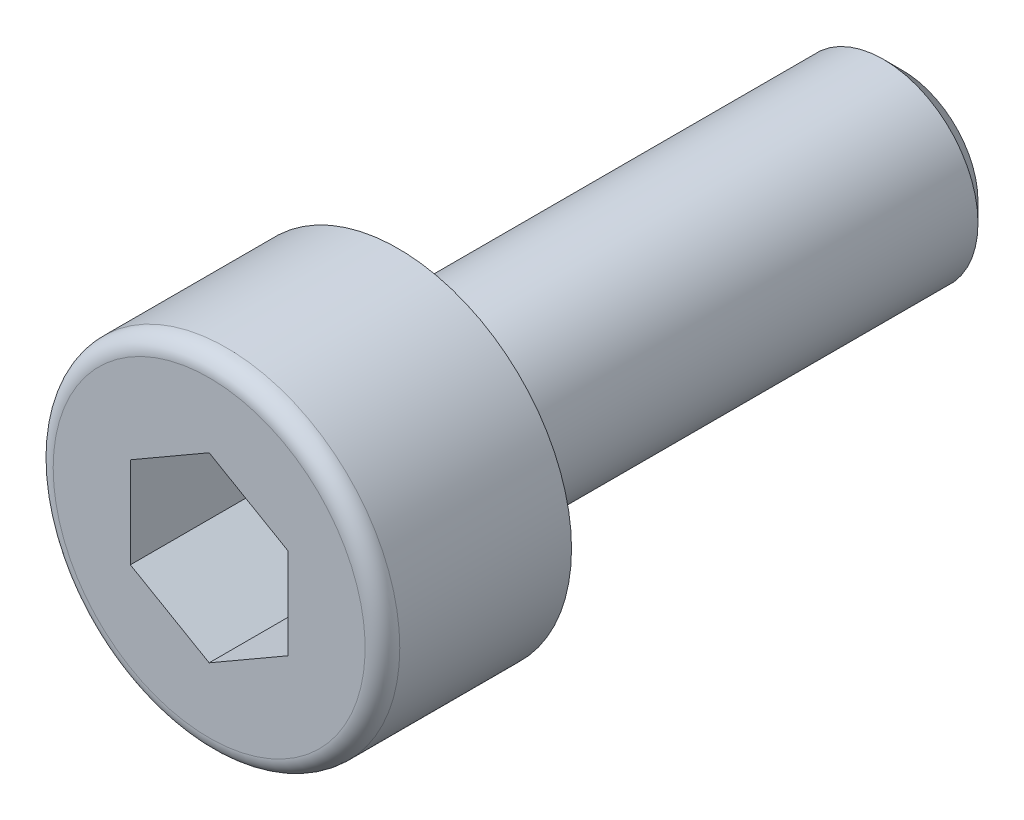
SolidWorks part; units mm, degrees
material "普通碳钢"
ref_plane "前视基准面" through (0, 0, 0) normal (0, 0, 1) x (1, 0, 0)
ref_plane "上视基准面" through (0, 0, 0) normal (0, 1, 0) x (1, 0, 0)
ref_plane "右视基准面" through (0, 0, 0) normal (1, 0, 0) x (0, 0, -1)
sketch "草图1" plane through (0, 0, 0) normal (1, 0, 0) x (0, 0, -1)
  line L0 (-3, 0) -> (30, 0) construction
  line L1 (-3, 0) -> (-3, 2.75)
  line L2 (-3, 2.75) -> (0, 2.75)
  line L3 (0, 2.75) -> (0, 1.5)
  line L4 (0, 1.5) -> (30, 1.5)
  line L5 (30, 1.5) -> (30, 0)
  point P3 (12, 1.5)
  dimension "A" = 5.5
  dimension "E" = 3
  dimension "L" = 30
  dimension "(e)" = 18
  dimension "M" = 3
sketch "草图2" plane through (0, 0, 0) normal (0, 0, 1) x (1, 0, 0)
  line L1 (0, 1.4434) -> (-1.25, 0.7217)
  line L2 (-1.25, 0.7217) -> (-1.25, -0.7217)
  line L3 (-1.25, -0.7217) -> (0, -1.4434)
  line L4 (0, -1.4434) -> (1.25, -0.7217)
  line L5 (1.25, -0.7217) -> (1.25, 0.7217)
  line L6 (1.25, 0.7217) -> (0, 1.4434)
  circle A0 centre (0, 0) radius 1.25 construction
  dimension "B" = 2.5
sketch "草图3" plane through (0, 0, 0) normal (1, 0, 0) x (0, 0, -1)
  line L0 (-3, 0) -> (-3, 2.75) construction
  line L1 (-3, 2.75) -> (0, 2.75) construction
  line L3 (0, 2.75) -> (0, 1.5) construction
  line L6 (-3, 0) -> (-3, 2.75)
  line L7 (-3, 2.75) -> (0, 2.75)
  line L8 (0, 1.5) -> (8, 1.5)
  line L9 (0, 2.75) -> (0, 1.5)
  line L10 (-3, 0) -> (8, 0)
  line L11 (8, 1.5) -> (8, 0)
  dimension "D1" = 8
revolve "旋转1" add sketch "草图3" angle 360 about L10
cosmetic thread "装饰螺纹线1" parameters "D2"=2.459
sketch "草图4" plane through (0, 0, 3) normal (0, 0, 1) x (1, 0, 0)
  line L0 (0, 1.4434) -> (-1.25, 0.7217) construction
  line L1 (-1.25, 0.7217) -> (-1.25, -0.7217) construction
  line L2 (-1.25, -0.7217) -> (0, -1.4434) construction
  line L3 (0, -1.4434) -> (1.25, -0.7217) construction
  line L4 (1.25, -0.7217) -> (1.25, 0.7217) construction
  line L5 (1.25, 0.7217) -> (0, 1.4434) construction
  line L6 (0, 1.4434) -> (-1.25, 0.7217)
  line L7 (-1.25, 0.7217) -> (-1.25, -0.7217)
  line L8 (-1.25, -0.7217) -> (0, -1.4434)
  line L9 (0, -1.4434) -> (1.25, -0.7217)
  line L10 (1.25, -0.7217) -> (1.25, 0.7217)
  line L11 (1.25, 0.7217) -> (0, 1.4434)
extrude "切除-拉伸1" cut sketch "草图4" against normal blind 1.925
fillet "圆角1" radius 0.275 1 edges at (2.75, 0, 3)
chamfer "倒角1" distance 0.3 angle 45 1 edges at (1.5, 0, -8)
